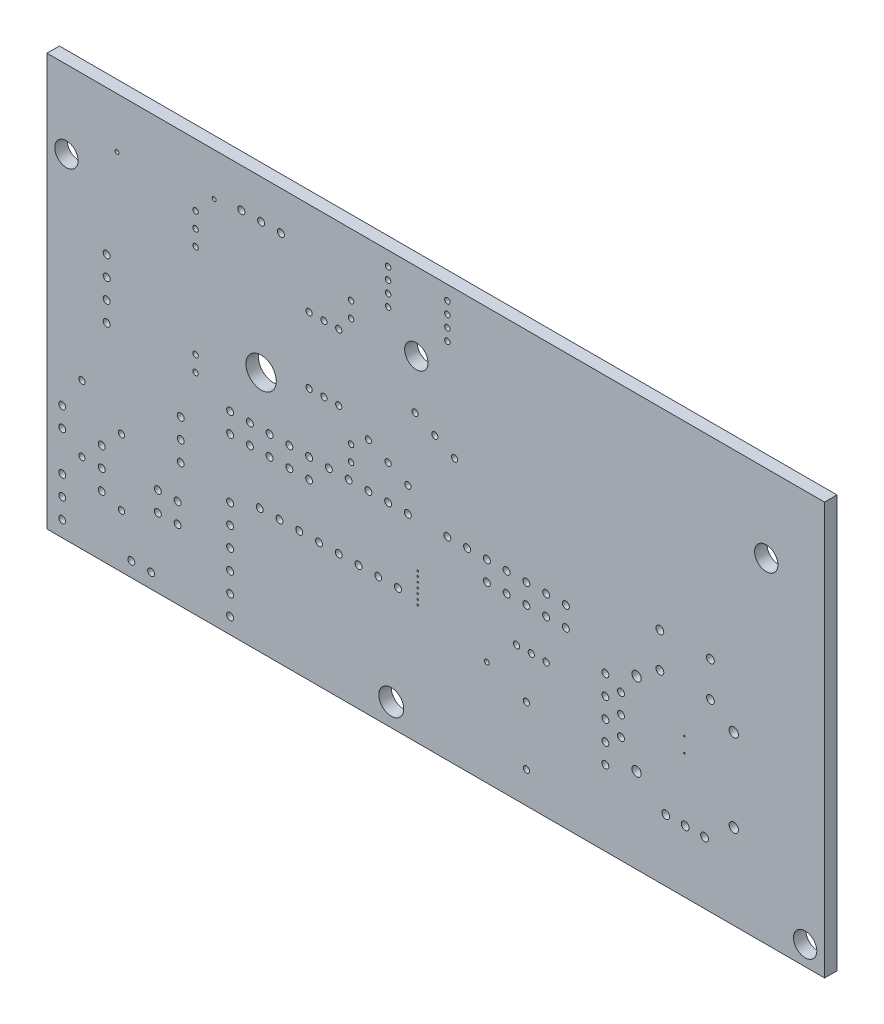
SolidWorks part; units mm, degrees
ref_plane "Front Plane" through (0, 0, 0) normal (0, 0, 1) x (1, 0, 0)
ref_plane "Top Plane" through (0, 0, 0) normal (0, 1, 0) x (1, 0, 0)
ref_plane "Right Plane" through (0, 0, 0) normal (1, 0, 0) x (0, 0, -1)
sketch "Model" plane through (0, 0, 0) normal (0, 0, 1) x (1, 0, 0)
  line L0 (440, 445) -> (540, 445)
  line L1 (540, 445) -> (540, 498)
  line L2 (540, 498) -> (440, 498)
  line L3 (440, 498) -> (440, 445)
  circle A0 centre (496.57, 458.47) radius 0.305
  circle A1 centre (461.5, 492.5) radius 0.25
  circle A2 centre (449, 491.5) radius 0.25
  circle A3 centre (453.39, 446.886) radius 0.4445
  circle A4 centre (450.85, 446.886) radius 0.4445
  circle A5 centre (457.2, 461.01) radius 0.4445
  circle A6 centre (457.2, 463.55) radius 0.4445
  circle A7 centre (457.2, 466.09) radius 0.4445
  circle A8 centre (447.675, 479.425) radius 0.4445
  circle A9 centre (447.675, 476.885) radius 0.4445
  circle A10 centre (447.675, 474.345) radius 0.4445
  circle A11 centre (447.675, 471.805) radius 0.4445
  circle A12 centre (447.04, 457.835) radius 0.4445
  circle A13 centre (447.04, 455.295) radius 0.4445
  circle A14 centre (447.04, 452.755) radius 0.4445
  circle A15 centre (441.96, 459.74) radius 0.4445
  circle A16 centre (441.96, 457.2) radius 0.4445
  circle A17 centre (449.58, 451.875) radius 0.4
  circle A18 centre (449.58, 460.375) radius 0.4
  circle A19 centre (444.5, 463.795) radius 0.4
  circle A20 centre (444.5, 455.295) radius 0.4
  circle A21 centre (494.03, 469.9) radius 0.4445
  circle A22 centre (491.49, 469.9) radius 0.4445
  circle A23 centre (496.57, 467.36) radius 0.4445
  circle A24 centre (496.57, 469.9) radius 0.4445
  circle A25 centre (467.54, 476.2) radius 1.95
  circle A26 centre (470.08, 493) radius 0.45
  circle A27 centre (467.54, 493) radius 0.45
  circle A28 centre (465, 493) radius 0.45
  circle A29 centre (456.797, 453.94) radius 0.4445
  circle A30 centre (454.257, 453.94) radius 0.4445
  circle A31 centre (454.257, 456.48) radius 0.4445
  circle A32 centre (456.797, 456.48) radius 0.4445
  circle A33 centre (441.96, 447.04) radius 0.4445
  circle A34 centre (441.96, 449.58) radius 0.4445
  circle A35 centre (441.96, 452.12) radius 0.4445
  circle A36 centre (484.27, 447.89) radius 1.6
  circle A37 centre (485.14, 461.01) radius 0.4445
  circle A38 centre (482.6, 461.01) radius 0.4445
  circle A39 centre (480.06, 461.01) radius 0.4445
  circle A40 centre (477.52, 461.01) radius 0.4445
  circle A41 centre (474.98, 461.01) radius 0.4445
  circle A42 centre (472.44, 461.01) radius 0.4445
  circle A43 centre (469.9, 461.01) radius 0.4445
  circle A44 centre (467.36, 461.01) radius 0.4445
  circle A45 centre (473.71, 486.02) radius 0.4
  circle A46 centre (473.71, 477.52) radius 0.4
  circle A47 centre (492.42, 479.085) radius 0.4
  circle A48 centre (486.41, 473.075) radius 0.4
  circle A49 centre (489.88, 480.355) radius 0.4
  circle A50 centre (483.87, 474.345) radius 0.4
  circle A51 centre (475.615, 486.02) radius 0.4
  circle A52 centre (475.615, 477.52) radius 0.4
  circle A53 centre (477.52, 486.02) radius 0.4
  circle A54 centre (477.52, 477.52) radius 0.4
  circle A55 centre (487.34, 481.625) radius 0.4
  circle A56 centre (481.33, 475.615) radius 0.4
  circle A57 centre (491.49, 496.165) radius 0.35
  circle A58 centre (491.49, 494.665) radius 0.35
  circle A59 centre (491.49, 493.165) radius 0.35
  circle A60 centre (491.49, 491.665) radius 0.35
  circle A61 centre (483.87, 496.165) radius 0.35
  circle A62 centre (483.87, 494.665) radius 0.35
  circle A63 centre (483.87, 493.165) radius 0.35
  circle A64 centre (483.87, 491.665) radius 0.35
  circle A65 centre (459.105, 488) radius 0.35
  circle A66 centre (459.105, 486) radius 0.35
  circle A67 centre (459.105, 490) radius 0.35
  circle A68 centre (479.105, 488) radius 0.35
  circle A69 centre (479.105, 490) radius 0.35
  circle A70 centre (479.105, 472) radius 0.35
  circle A71 centre (479.105, 474) radius 0.35
  circle A72 centre (459.105, 474) radius 0.35
  circle A73 centre (459.105, 472) radius 0.35
  circle A74 centre (501.65, 449.065) radius 0.4
  circle A75 centre (501.65, 456.565) radius 0.4
  circle A76 centre (500.38, 462.28) radius 0.4065
  circle A77 centre (502.285, 462.28) radius 0.4065
  circle A78 centre (504.19, 462.28) radius 0.4065
  circle A79 centre (518.82, 473.18) radius 0.5
  circle A80 centre (525.32, 473.18) radius 0.5
  circle A81 centre (525.32, 468.68) radius 0.5
  circle A82 centre (518.82, 468.68) radius 0.5
  circle A83 centre (513.82, 463.73) radius 0.4445
  circle A84 centre (513.82, 461.23) radius 0.4445
  circle A85 centre (513.82, 458.73) radius 0.4445
  circle A86 centre (528.32, 466.53) radius 0.6
  circle A87 centre (515.82, 466.53) radius 0.6
  circle A88 centre (515.82, 455.93) radius 0.6
  circle A89 centre (528.32, 455.93) radius 0.6
  circle A90 centre (519.57, 452.98) radius 0.5
  circle A91 centre (522.07, 452.98) radius 0.5
  circle A92 centre (524.57, 452.98) radius 0.5
  circle A93 centre (511.81, 457.2) radius 0.4445
  circle A94 centre (511.81, 459.74) radius 0.4445
  circle A95 centre (511.81, 462.28) radius 0.4445
  circle A96 centre (511.81, 464.82) radius 0.4445
  circle A97 centre (463.55, 447.04) radius 0.4445
  circle A98 centre (463.55, 449.58) radius 0.4445
  circle A99 centre (463.55, 452.12) radius 0.4445
  circle A100 centre (463.55, 454.66) radius 0.4445
  circle A101 centre (463.55, 457.2) radius 0.4445
  circle A102 centre (463.55, 459.74) radius 0.4445
  circle A103 centre (506.73, 467.36) radius 0.4445
  circle A104 centre (504.19, 467.36) radius 0.4445
  circle A105 centre (501.65, 467.36) radius 0.4445
  circle A106 centre (499.11, 467.36) radius 0.4445
  circle A107 centre (506.73, 469.9) radius 0.4445
  circle A108 centre (504.19, 469.9) radius 0.4445
  circle A109 centre (501.65, 469.9) radius 0.4445
  circle A110 centre (499.11, 469.9) radius 0.4445
  circle A111 centre (486.41, 469.9) radius 0.4445
  circle A112 centre (483.87, 469.9) radius 0.4445
  circle A113 centre (481.33, 469.9) radius 0.4445
  circle A114 centre (478.79, 469.9) radius 0.4445
  circle A115 centre (476.25, 469.9) radius 0.4445
  circle A116 centre (473.71, 467.36) radius 0.4445
  circle A117 centre (471.17, 467.36) radius 0.4445
  circle A118 centre (468.63, 467.36) radius 0.4445
  circle A119 centre (466.09, 467.36) radius 0.4445
  circle A120 centre (463.55, 467.36) radius 0.4445
  circle A121 centre (473.71, 469.9) radius 0.4445
  circle A122 centre (471.17, 469.9) radius 0.4445
  circle A123 centre (468.63, 469.9) radius 0.4445
  circle A124 centre (466.09, 469.9) radius 0.4445
  circle A125 centre (463.55, 469.9) radius 0.4445
  circle A126 centre (487.5, 488) radius 1.5
  circle A127 centre (442.5, 488) radius 1.5
  circle A128 centre (532.5, 488) radius 1.5
  circle A129 centre (537.5, 447.5) radius 1.5
  circle A130 centre (511.81, 454.66) radius 0.4445
  circle A131 centre (521.97, 461.01) radius 0.1
  circle A132 centre (521.97, 462.915) radius 0.1
  circle A133 centre (487.68, 464.185) radius 0.1
  circle A134 centre (487.68, 463.55) radius 0.1
  circle A135 centre (487.68, 462.915) radius 0.1
  circle A136 centre (487.68, 462.28) radius 0.1
  circle A137 centre (487.68, 461.01) radius 0.1
  circle A138 centre (487.68, 460.375) radius 0.1
  circle A139 centre (487.68, 461.645) radius 0.1
extrude "Boss-Extrude1" add sketch "Model" along normal blind 1.6
sketch "Sketch1" plane through (0, 0, 1.6) normal (0, 0, 1) x (1, 0, 0)
  line L0 (487.68, 460.375) -> (487.68, 498)
  line L1 (540, 498) -> (440, 498) construction
  line L2 (487.68, 498) -> (487.68, 445)
  line L3 (440, 445) -> (540, 445) construction
  line L4 (515.82, 466.53) -> (528.32, 455.93)
  line L5 (528.32, 466.53) -> (515.82, 455.93)
  point P16 (522.07, 461.23)
